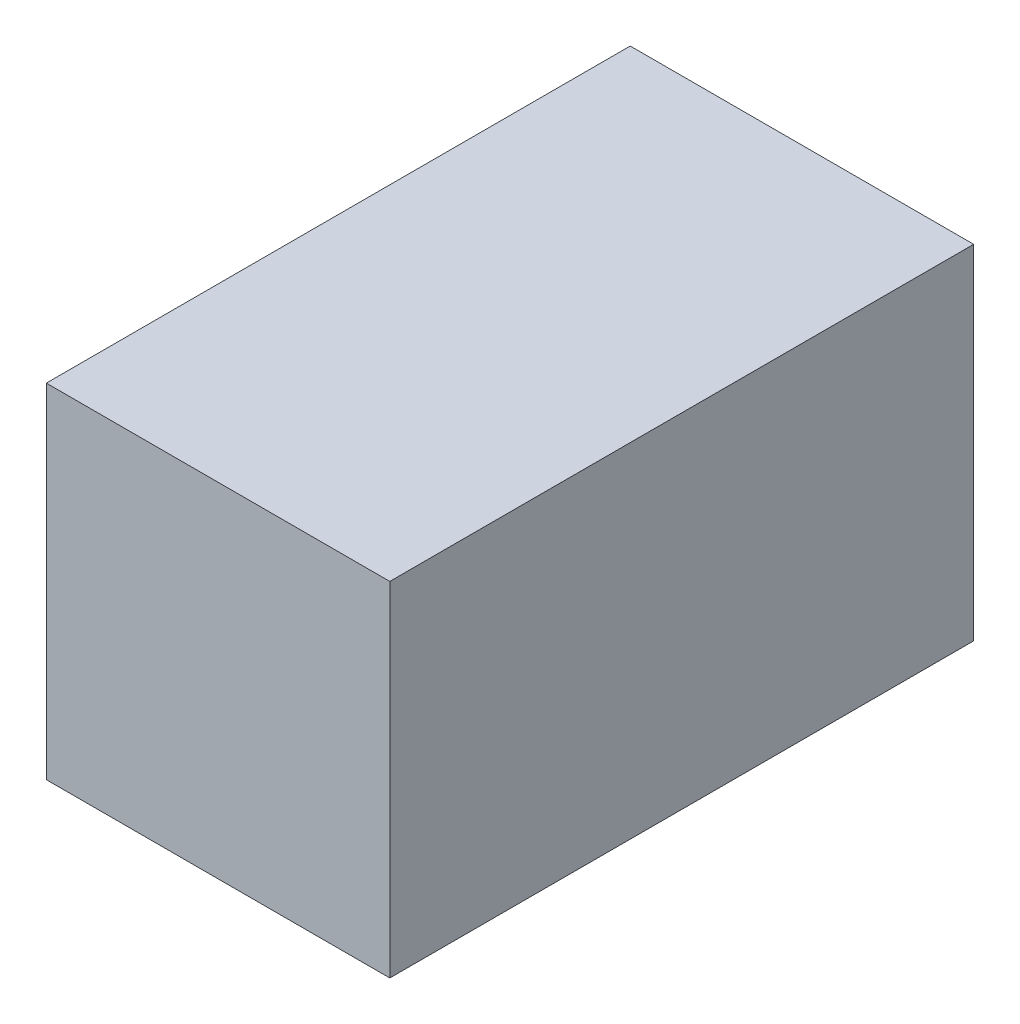
SolidWorks part; units mm, degrees
ref_plane "前视基准面" through (0, 0, 0) normal (0, 0, 1) x (1, 0, 0)
ref_plane "上视基准面" through (0, 0, 0) normal (0, 1, 0) x (1, 0, 0)
ref_plane "右视基准面" through (0, 0, 0) normal (1, 0, 0) x (0, 0, -1)
other "Configuration Table"
sketch "草图1" plane through (0, 0, 0) normal (0, 0, 1) x (1, 0, 0)
  line L1 (0, 0) -> (10, 0)
  line L2 (0, 0) -> (0, 10)
  line L3 (0, 10) -> (10, 10)
  line L4 (10, 0) -> (10, 10)
extrude "凸台-拉伸1" add sketch "草图1" along normal blind 10 and the other way blind 7
